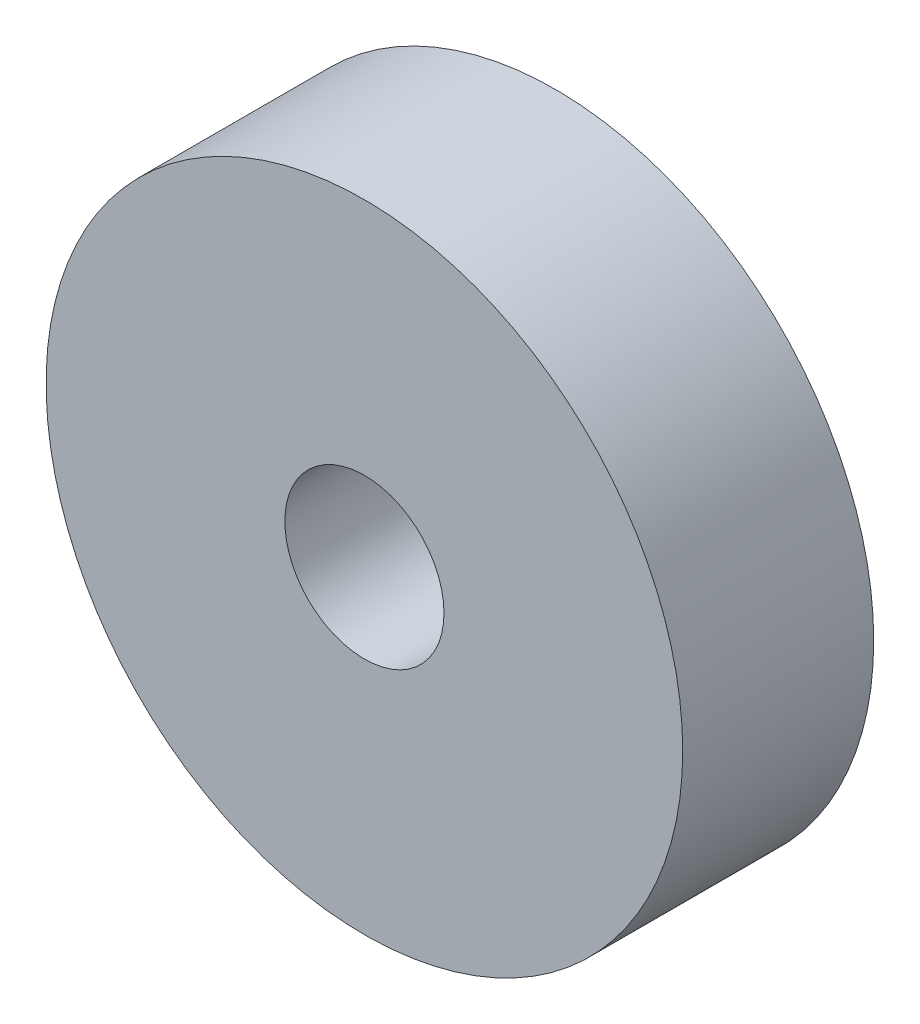
SolidWorks part; units mm, degrees
ref_plane "Front Plane" through (0, 0, 0) normal (0, 0, 1) x (1, 0, 0)
ref_plane "Top Plane" through (0, 0, 0) normal (0, 1, 0) x (1, 0, 0)
ref_plane "Right Plane" through (0, 0, 0) normal (1, 0, 0) x (0, 0, -1)
sketch "Sketch1" plane through (0, 0, 0) normal (0, 0, 1) x (1, 0, 0)
  circle A0 centre (0, 0) radius 1.25
  circle A1 centre (0, 0) radius 5
  dimension "D1" = 2.5
  dimension "D2" = 10
extrude "Boss-Extrude1" add sketch "Sketch1" along normal blind 3
